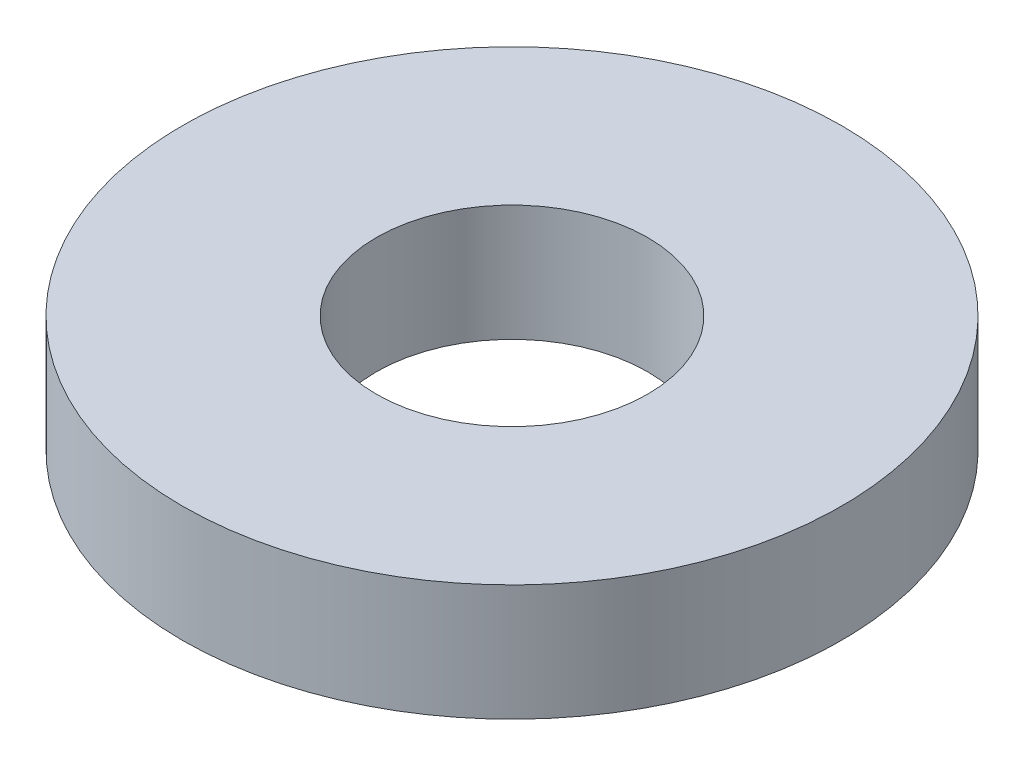
SolidWorks part; units mm, degrees
ref_plane "Front Plane" through (0, 0, 0) normal (0, 0, 1) x (1, 0, 0)
ref_plane "Top Plane" through (0, 0, 0) normal (0, 1, 0) x (1, 0, 0)
ref_plane "Right Plane" through (0, 0, 0) normal (1, 0, 0) x (0, 0, -1)
sketch "Sketch2" plane through (0, 0, 0) normal (0, 1, 0) x (1, 0, 0)
  circle A0 centre (0, 0) radius 17
  circle A1 centre (0, 0) radius 7
  dimension "D1" = 34
extrude "Boss-Extrude1" add sketch "Sketch2" along normal blind 6
